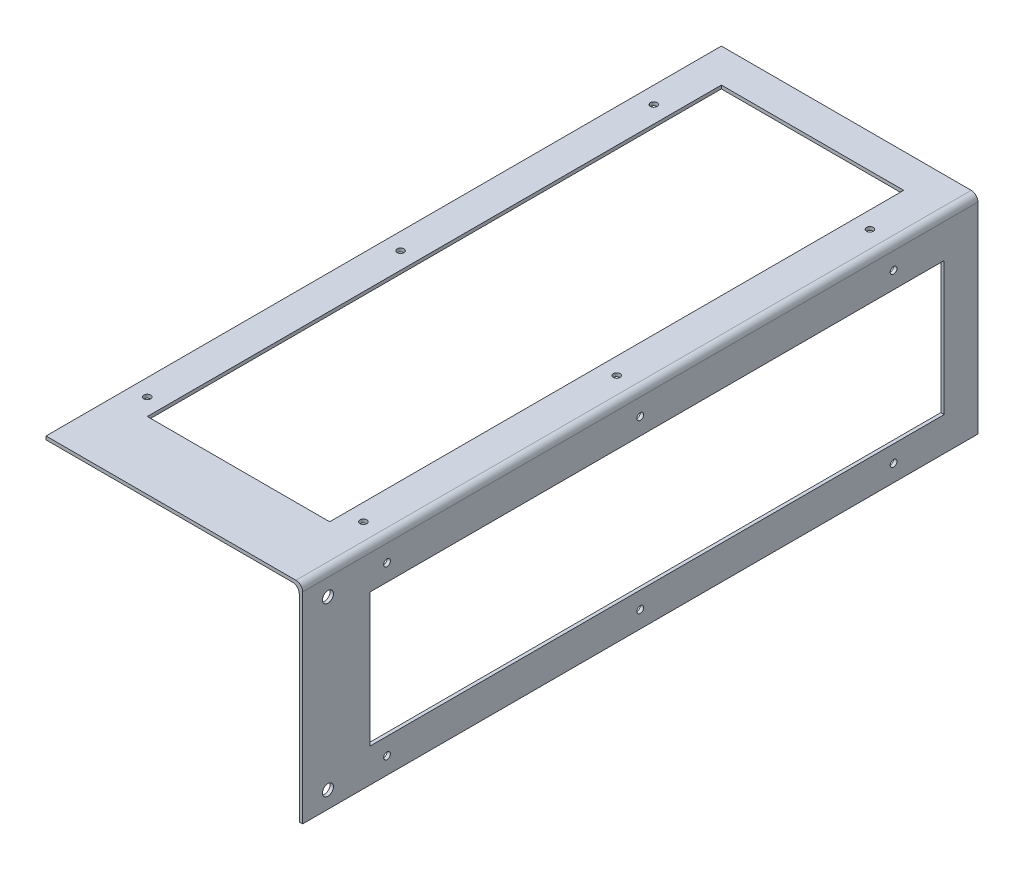
SolidWorks part; units mm, degrees
material "6061 Alloy"
ref_plane "Front Plane" through (0, 0, 0) normal (0, 0, 1) x (1, 0, 0)
ref_plane "Top Plane" through (0, 0, 0) normal (0, 1, 0) x (1, 0, 0)
ref_plane "Right Plane" through (0, 0, 0) normal (1, 0, 0) x (0, 0, -1)
sketch "Sketch1" plane through (0, 0, 0) normal (0, 0, 1) x (1, 0, 0)
  line L0 (0, 0) -> (0, -2)
  line L1 (0, -2) -> (146, -2)
  line L2 (150, -6) -> (150, -123)
  line L3 (150, -123) -> (152, -123)
  line L4 (152, -123) -> (152, -4)
  line L5 (148, 0) -> (0, 0)
  arc A0 (150, -6) -> (146, -2) centre (146, -6) ccw
  arc A1 (152, -4) -> (148, 0) centre (148, -4) ccw
  point P13 (152, 0)
  dimension "D5" = 4
  dimension "D1" = 2
  dimension "D2" = 2
  dimension "D3" = 152
  dimension "D4" = 123
extrude "Boss-Extrude1" add sketch "Sketch1" along normal blind 400
sketch "Sketch3" plane through (152, 0, 0) normal (1, 0, 0) x (0, 0, -1)
  line L0 (0, -123) -> (0, -4) construction
  line L2 (-400, -123) -> (0, -123) construction
  line L3 (-360, -24) -> (-20, -24)
  line L4 (-360, -24) -> (-360, -103)
  line L5 (-360, -103) -> (-20, -103)
  line L6 (-20, -24) -> (-20, -103)
  line L7 (-360, -24) -> (-20, -103) construction
  line L8 (-360, -103) -> (-20, -24) construction
  line L9 (-400, -4) -> (0, -4) construction
  line L10 (-400, -123) -> (-400, -4) construction
  point P4 (-190, -63.5)
  dimension "D1" = 20
  dimension "D2" = 20
  dimension "D3" = 20
  dimension "D4" = 40
extrude "Cut-Extrude1" cut sketch "Sketch3" against normal blind 2
sketch "Sketch4" plane through (0, 0, 0) normal (0, 1, 0) x (1, 0, 0)
  line L0 (148, 0) -> (0, 0) construction
  line L1 (20, -360) -> (128, -360)
  line L2 (20, -360) -> (20, -20)
  line L3 (20, -20) -> (128, -20)
  line L4 (128, -360) -> (128, -20)
  line L5 (20, -360) -> (128, -20) construction
  line L6 (20, -20) -> (128, -360) construction
  line L7 (0, -400) -> (0, 0) construction
  line L8 (148, -400) -> (148, 0) construction
  line L9 (148, -400) -> (0, -400) construction
  point P0 (74, -190)
  dimension "D1" = 20
  dimension "D2" = 20
  dimension "D3" = 20
  dimension "D4" = 40
extrude "Cut-Extrude2" cut sketch "Sketch4" against normal blind 2
sketch "Sketch6" plane through (152, 0, 0) normal (1, 0, 0) x (0, 0, -1)
  line L0 (-400, -123) -> (0, -123) construction
  line L1 (-400, -123) -> (-400, -4) construction
  line L2 (-385, -113) -> (-385, -14) construction
  circle A0 centre (-385, -14) radius 3.25
  circle A1 centre (-385, -113) radius 3.25
  dimension "D1" = 6.5
  dimension "D2" = 6.5
  dimension "D4" = 15
  dimension "D3" = 10
  dimension "D5" = 99
extrude "Cut-Extrude3" cut sketch "Sketch6" against normal blind 2
sketch "Sketch7" plane through (0, 0, 0) normal (0, 1, 0) x (1, 0, 0)
  line L0 (148, 0) -> (0, 0) construction
  line L1 (20, -20) -> (20, -360) construction
  line L2 (128, -360) -> (128, -20) construction
  circle A0 centre (10, -50) radius 2
  circle A1 centre (10, -200) radius 2
  circle A2 centre (10, -350) radius 2
  circle A3 centre (138, -50) radius 2
  circle A4 centre (138, -200) radius 2
  circle A5 centre (138, -350) radius 2
  dimension "D1" = 50
  dimension "D3" = 4
  dimension "D4" = 10
  dimension "D5" = 4
  dimension "D7" = 10
  dimension "D8" = 4
  dimension "D11" = 4
  dimension "D12" = 50
  dimension "D13" = 4
  dimension "D15" = 150
  dimension "D16" = 4
  dimension "D18" = 150
  dimension "D2" = 10
  dimension "D6" = 150
  dimension "D9" = 150
  dimension "D10" = 10
  dimension "D14" = 10
  dimension "D17" = 10
extrude "Cut-Extrude4" cut sketch "Sketch7" against normal blind 2
sketch "Sketch8" plane through (152, 0, 0) normal (1, 0, 0) x (0, 0, -1)
  line L0 (0, -123) -> (0, -4) construction
  line L1 (-360, -103) -> (-20, -103) construction
  line L2 (-20, -63.5) -> (-360, -63.5) construction
  line L3 (-20, -103) -> (-20, -24) construction
  line L4 (-360, -24) -> (-360, -103) construction
  circle A0 centre (-50, -113) radius 2
  circle A1 centre (-200, -113) radius 2
  circle A2 centre (-350, -113) radius 2
  circle A3 centre (-350, -14) radius 2
  circle A4 centre (-200, -14) radius 2
  circle A5 centre (-50, -14) radius 2
  dimension "D1" = 4
  dimension "D2" = 50
  dimension "D3" = 10
  dimension "D4" = 3
extrude "Cut-Extrude5" cut sketch "Sketch8" against normal blind 2
